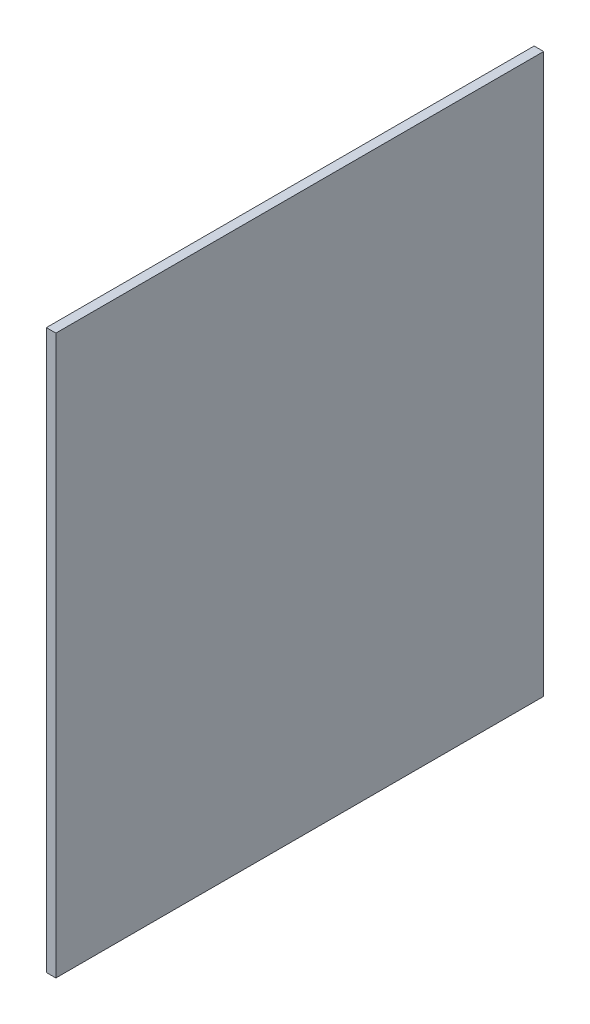
SolidWorks part; units mm, degrees
ref_plane "Front Plane" through (0, 0, 0) normal (0, 0, 1) x (1, 0, 0)
ref_plane "Top Plane" through (0, 0, 0) normal (0, 1, 0) x (1, 0, 0)
ref_plane "Right Plane" through (0, 0, 0) normal (1, 0, 0) x (0, 0, -1)
sketch "Sketch1" plane through (0, 0, 0) normal (1, 0, 0) x (0, 0, -1)
  line L1 (0, 0) -> (130.3, 0)
  line L2 (0, 0) -> (0, 149.2)
  line L3 (0, 149.2) -> (130.3, 149.2)
  line L4 (130.3, 0) -> (130.3, 149.2)
  dimension "D1" = 130.3
  dimension "D2" = 149.2
extrude "Boss-Extrude1" add sketch "Sketch1" along normal blind 2.54
